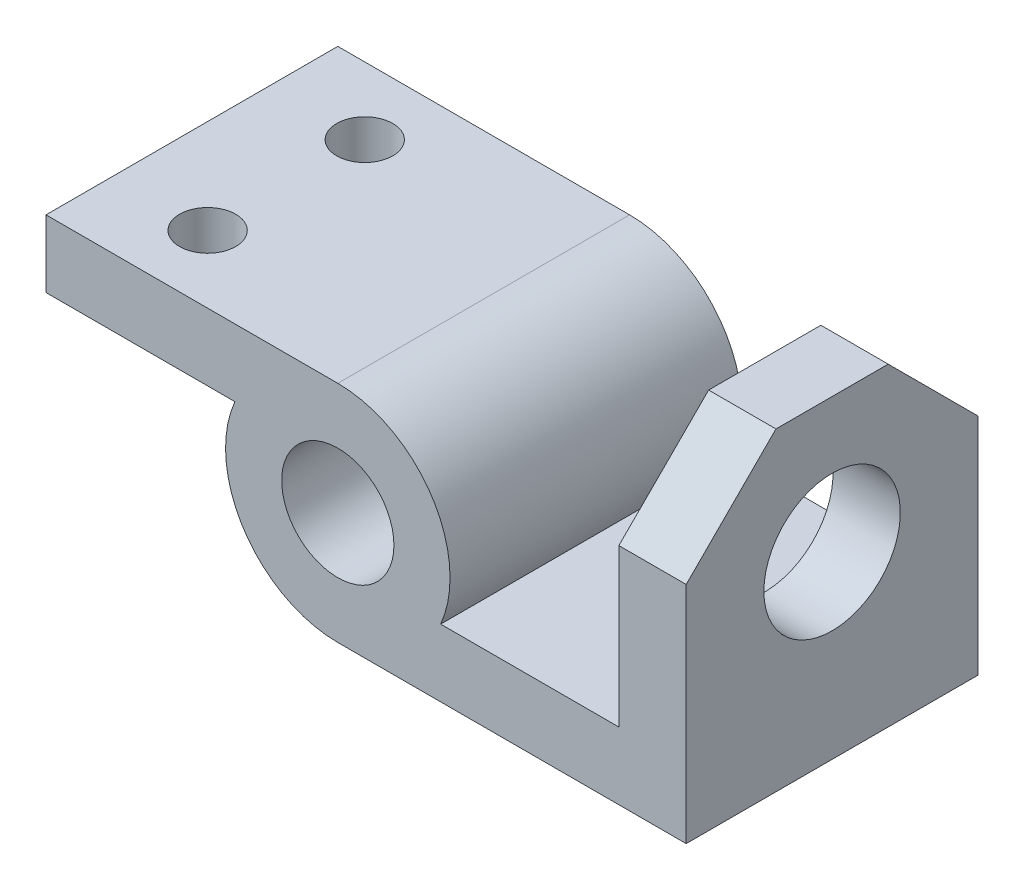
SolidWorks part; units mm, degrees
other "Markup1"
sketch "Sketch4" plane through (-82.55, 57.15, 82.55) normal (-0.1101, 0.0308, 0.9934) x (0.9939, 0, 0.1102)
ref_plane "Front Plane" through (0, 0, 0) normal (0, 0, 1) x (1, 0, 0)
ref_plane "Top Plane" through (0, 0, 0) normal (0, 1, 0) x (1, 0, 0)
ref_plane "Right Plane" through (0, 0, 0) normal (1, 0, 0) x (0, 0, -1)
sketch "Sketch1" plane through (0, 0, 0) normal (0, 0, 1) x (1, 0, 0)
  line L6 (0, 31.75) -> (-82.55, 31.75)
  line L7 (-82.55, 31.75) -> (-82.55, 12.7)
  line L8 (-82.55, 12.7) -> (-29.0994, 12.7)
  line L9 (0, -31.75) -> (79.502, -31.75)
  line L10 (79.502, -31.75) -> (79.502, -12.7)
  line L11 (79.502, -12.7) -> (29.0994, -12.7)
  circle A3 centre (0, 0) radius 15.875
  circle A4 centre (0, 0) radius 31.75
  dimension "D3" = 31.75
  dimension "D2" = 63.5
  dimension "D1" = 79.502
  dimension "D4" = 162.052
  dimension "D5" = 19.05
  dimension "D6" = 19.05
extrude "Boss-Extrude1" add sketch "Sketch1" along normal blind 82.55 contours A4 L6 L7 L8 | A4 A3 | A4 L9 L10 L11
ref_plane "Plane1" through (79.502, 0, 0) normal (1, 0, 0) x (0, 0, -1)
sketch "Sketch2" plane through (79.502, 0, 0) normal (1, 0, 0) x (0, 0, -1)
  line L0 (-82.55, -31.75) -> (0, -31.75)
  line L1 (0, -31.75) -> (0, 31.75)
  line L2 (0, 31.75) -> (-25.4, 57.15)
  line L3 (-25.4, 57.15) -> (-57.15, 57.15)
  line L4 (-57.15, 57.15) -> (-82.55, 31.75)
  line L5 (-82.55, 31.75) -> (-82.55, -31.75)
  line L6 (-41.275, 57.15) -> (-41.275, -31.75) construction
  circle A0 centre (-41.275, 19.05) radius 19.304
  dimension "D6" = 38.608
  dimension "D1" = 25.4
  dimension "D2" = 25.4
  dimension "D3" = 88.9
  dimension "D4" = 38.1
  dimension "D5" = 41.275
extrude "Boss-Extrude2" add sketch "Sketch2" along normal blind 19.05
ref_plane "Plane2" through (0, 31.75, 0) normal (0, 1, 0) x (1, 0, 0)
sketch "Sketch3" plane through (0, 31.75, 0) normal (0, 1, 0) x (1, 0, 0)
  line L0 (0, -82.55) -> (-82.55, -82.55) construction
  line L1 (0, 0) -> (-82.55, 0) construction
  line L2 (-82.55, -82.55) -> (-82.55, 0) construction
  circle A0 centre (-55.88, -19.05) radius 7.9375
  circle A1 centre (-55.88, -63.5) radius 7.9375
  dimension "D5" = 15.875
  dimension "D6" = 15.875
  dimension "D1" = 19.05
  dimension "D2" = 19.05
  dimension "D3" = 26.67
  dimension "D4" = 26.67
extrude "Cut-Extrude1" cut sketch "Sketch3" against normal blind 19.05
